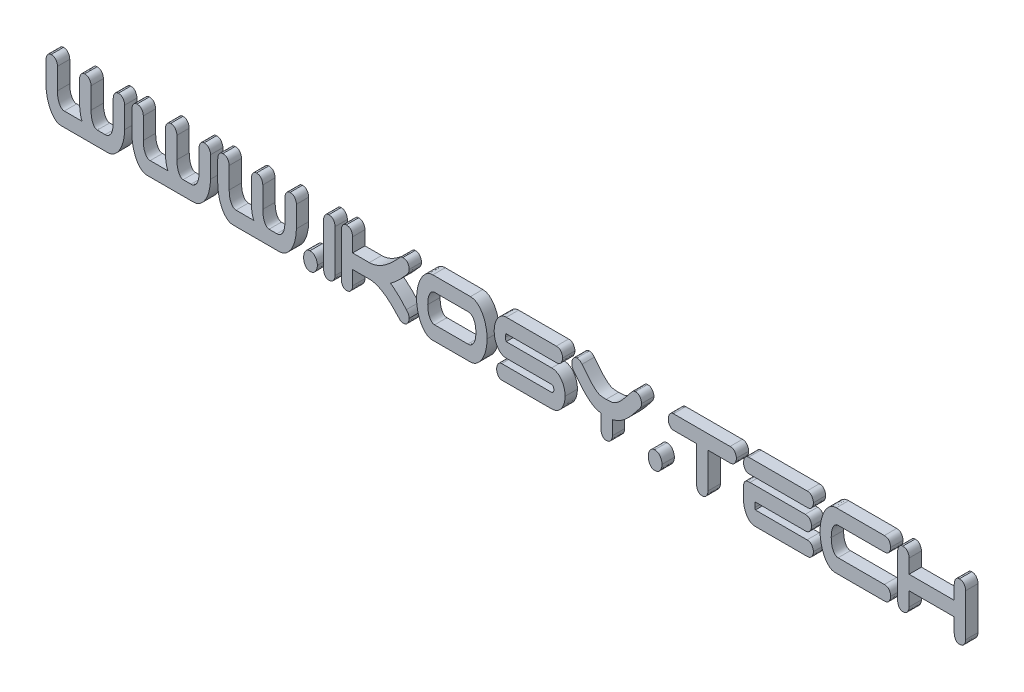
SolidWorks part; units mm, degrees
other "Text Extrude - W1"
other "Text Extrude - W2"
other "Text Extrude - W3"
other "Text Extrude - ."
other "Text Extrude - I" parameters "D1"=19.4587, "D2"=1.1925, "D3"=36.394, "D4"=188.1767, "D5"=2.5
ref_plane "Front Plane" through (0, 0, 0) normal (0, 0, 1) x (1, 0, 0)
ref_plane "Top Plane" through (0, 0, 0) normal (0, 1, 0) x (1, 0, 0)
ref_plane "Right Plane" through (0, 0, 0) normal (1, 0, 0) x (0, 0, -1)
sketch "Insertion Point Sketch" plane through (0, 0, 0) normal (0, 0, 1) x (1, 0, 0)
  line L0 (-2.5, -2.5) -> (-2.5, 0) construction
  line L1 (-2.5, -2.5) -> (0, -2.5) construction
  dimension "D1" = 2.5
  dimension "D2" = 2.5
ref_plane "3D Printing Base Plane" through (0, 0, -4) normal (0, 0, 1) x (1, 0, 0)
sketch "3D Printing Origin Sketch" plane through (0, 0, -4) normal (0, 0, 1) x (1, 0, 0)
  point P0 (-23.75, -5)
  dimension "D1" = 2.5
  dimension "D2" = 21.25
sketch "Text Sketch" plane through (0, 0, 0) normal (0, 0, 1) x (1, 0, 0)
  line L0 (-5, 15) -> (187.5, 15) construction
  line L1 (187.5, 15) -> (187.5, -5) construction
  line L2 (187.5, -5) -> (-5, -5) construction
  line L3 (187.5, 12.5) -> (-2.5, 12.5) construction
  line L4 (187.5, -2.5) -> (-2.5, -2.5) construction
  line L5 (-5, 15) -> (-5, -5) construction
  line L6 (-2.5, -2.5) -> (-2.5, 12.5) construction
  text T0 "www.ikosy.tech" font "Space Age" height 11.5
  dimension "D1" = 2.5
  dimension "D4" = 187.5
  dimension "D3" = 2.5
  dimension "D2" = 20
extrude "Text Extrude" add sketch "Text Sketch" along normal blind 2.5 separate body
equation "\"Logo Height\"= \"Total Height\" - 2 * \"Border\""
equation "\"Total Height\"= 20"
equation "\"Border\"= 2.5"
equation "\"D1@Insertion Point Sketch\" = \"Border\""
equation "\"D2@Insertion Point Sketch\" = \"Border\""
equation "\"D2@Text Sketch\"=\"Total Height\""
equation "\"D5@Text Sketch\"=\"Border\""
equation "\"D3@Text Sketch\"=\"Border\""
equation "\"D1@Text Sketch\"=\"Border\""
equation "\"D1@3D Printing Origin Sketch\"=\"Border\""
